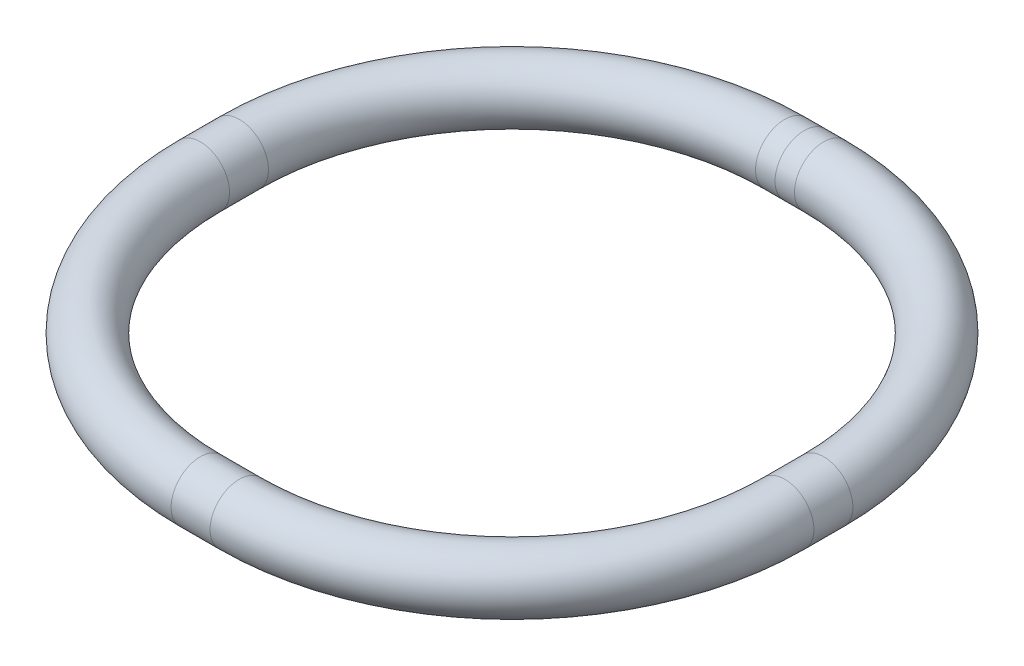
SolidWorks part; units mm, degrees
material "7075-T6 (SN)"
ref_plane "Front Plane" through (0, 0, 0) normal (0, 0, 1) x (1, 0, 0)
ref_plane "Top Plane" through (0, 0, 0) normal (0, 1, 0) x (1, 0, 0)
ref_plane "Right Plane" through (0, 0, 0) normal (1, 0, 0) x (0, 0, -1)
sketch "Sketch1" plane through (0, 0, 0) normal (0, 1, 0) x (1, 0, 0)
  line L1 (-0.5, -7.5) -> (0.5, -7.5)
  line L2 (-7.5, -0.5) -> (-7.5, 0.5)
  line L3 (-0.5, 7.5) -> (0.5, 7.5)
  line L4 (7.5, -0.5) -> (7.5, 0.5)
  line L5 (-7.5, -7.5) -> (7.5, 7.5) construction
  line L6 (-7.5, 7.5) -> (7.5, -7.5) construction
  arc A0 (-0.5, -7.5) -> (-7.5, -0.5) centre (-0.5, -0.5) cw
  arc A1 (-7.5, 0.5) -> (-0.5, 7.5) centre (-0.5, 0.5) cw
  arc A2 (0.5, -7.5) -> (7.5, -0.5) centre (0.5, -0.5) ccw
  arc A3 (7.5, 0.5) -> (0.5, 7.5) centre (0.5, 0.5) ccw
  point P0 (0, 0)
  dimension "D2" = 7
  dimension "D1" = 15
sketch "Sketch2" plane through (0, 0, 0) normal (1, 0, 0) x (0, 0, -1)
  circle A0 centre (7.5, 0) radius 0.75
  point P2 (0, 0)
  point P6 (0, 0)
  dimension "D1" = 1.5
  dimension "D2" = 7.5
sweep "Sweep1" add profiles "Sketch2" path "Sketch1"
